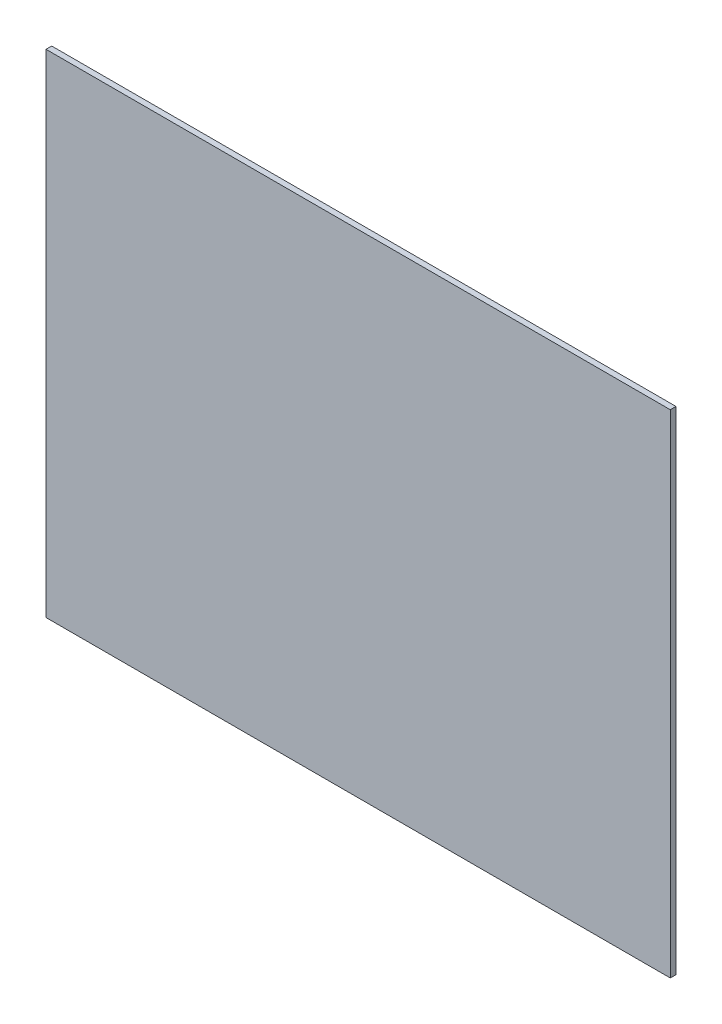
SolidWorks part; units mm, degrees
material "PVC 0.007 Plasticized"
ref_plane "Front Plane" through (0, 0, 0) normal (0, 0, 1) x (1, 0, 0)
ref_plane "Top Plane" through (0, 0, 0) normal (0, 1, 0) x (1, 0, 0)
ref_plane "Right Plane" through (0, 0, 0) normal (1, 0, 0) x (0, 0, -1)
sketch "Sketch2" plane through (0, 0, 0) normal (0, 0, 1) x (1, 0, 0)
  line L1 (-339.2991, 245.1916) -> (208.7009, 245.1916)
  line L2 (-339.2991, 245.1916) -> (-339.2991, -186.8084)
  line L3 (-339.2991, -186.8084) -> (208.7009, -186.8084)
  line L4 (208.7009, 245.1916) -> (208.7009, -186.8084)
  dimension "D1" = 548
  dimension "D2" = 432
extrude "Boss-Extrude1" add sketch "Sketch2" along normal blind 5
